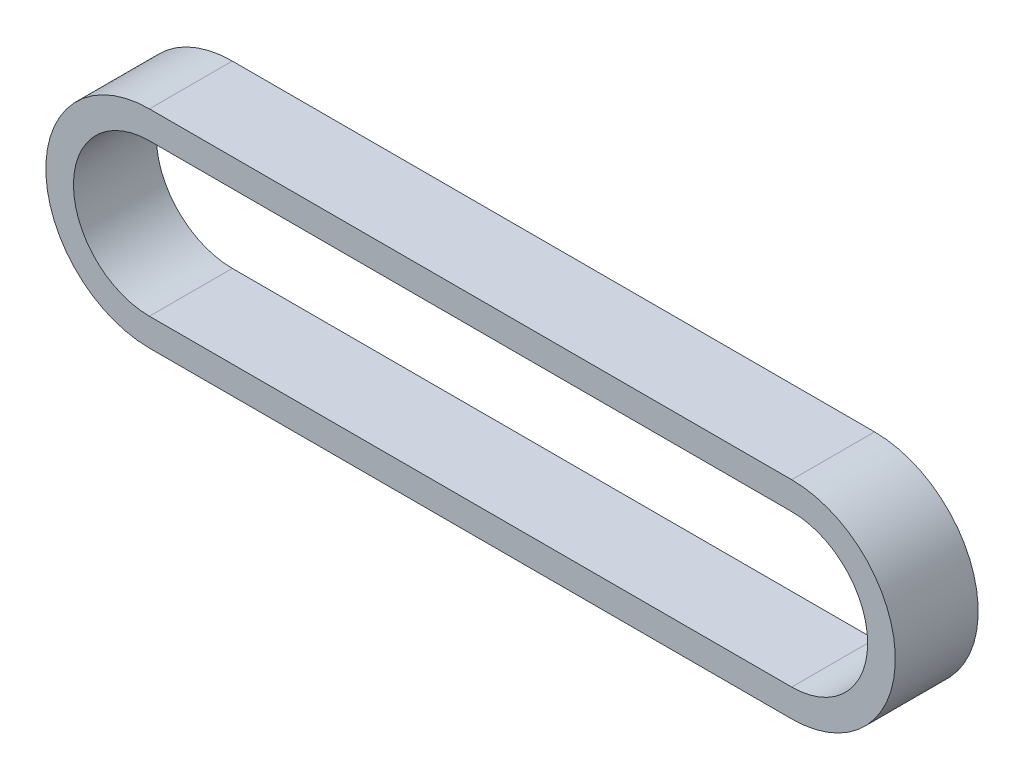
SolidWorks part; units mm, degrees
ref_plane "前视基准面" through (0, 0, 0) normal (0, 0, 1) x (1, 0, 0)
ref_plane "上视基准面" through (0, 0, 0) normal (0, 1, 0) x (1, 0, 0)
ref_plane "右视基准面" through (0, 0, 0) normal (1, 0, 0) x (0, 0, -1)
other "Configuration Table"
sketch "草图1" plane through (0, 0, 0) normal (0, 0, 1) x (1, 0, 0)
  line L0 (0, 0) -> (46.5, 0) construction
  line L1 (0, 5.5) -> (46.5, 5.5)
  line L2 (0, -5.5) -> (46.5, -5.5)
  line L3 (0, 0) -> (46.5, 0) construction
  line L4 (0, 7.5) -> (46.5, 7.5)
  line L5 (0, -7.5) -> (46.5, -7.5)
  arc A0 (0, 5.5) -> (0, -5.5) centre (0, 0) ccw
  arc A1 (46.5, -5.5) -> (46.5, 5.5) centre (46.5, 0) ccw
  arc A2 (0, 7.5) -> (0, -7.5) centre (0, 0) ccw
  arc A3 (46.5, -7.5) -> (46.5, 7.5) centre (46.5, 0) ccw
  point P3 (23.25, 0)
  point P10 (23.25, 0)
  dimension "D2" = 5.5
  dimension "D1" = 46.5
  dimension "D3" = 2
extrude "凸台-拉伸1" add sketch "草图1" along normal blind 6
